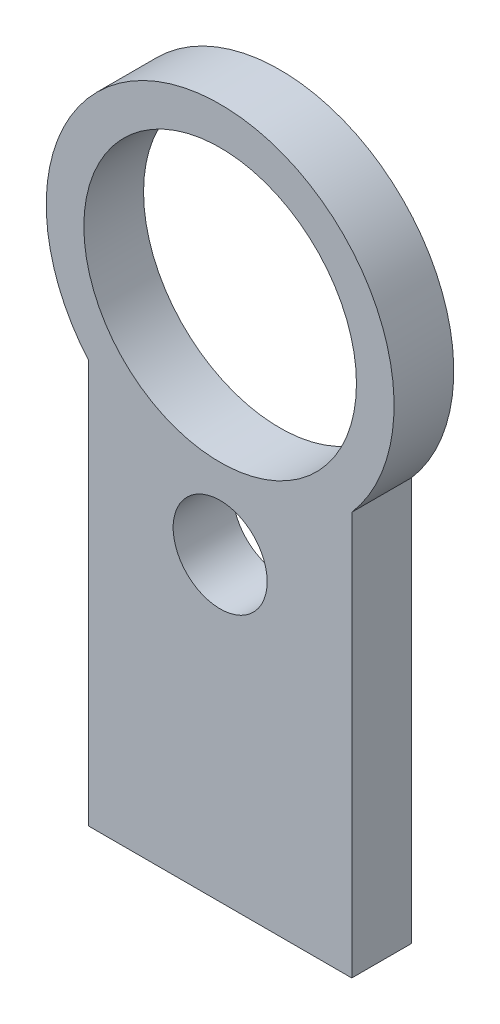
SolidWorks part; units mm, degrees
ref_plane "Front Plane" through (0, 0, 0) normal (0, 0, 1) x (1, 0, 0)
ref_plane "Top Plane" through (0, 0, 0) normal (0, 1, 0) x (1, 0, 0)
ref_plane "Right Plane" through (0, 0, 0) normal (1, 0, 0) x (0, 0, -1)
sketch "Sketch1" plane through (0, 0, 0) normal (0, 0, 1) x (1, 0, 0)
  line L1 (-14, -55) -> (14, -55)
  line L3 (0, -55) -> (0, 55) construction
  line L4 (-14, -55) -> (-14, -12.0934)
  line L5 (14, -55) -> (14, -12.0934)
  circle A3 centre (0, 0) radius 14.5
  arc A5 (-14, -12.0934) -> (14, -12.0934) centre (0, 0) cw
  circle A6 centre (0, -23) radius 5
  point P3 (0, -55)
  dimension "D1" = 28
  dimension "D3" = 29
  dimension "D4" = 18.5
  dimension "D2" = 55
  dimension "D5" = 10
  dimension "D6" = 32
extrude "Boss-Extrude1" add sketch "Sketch1" along normal blind 6.35
